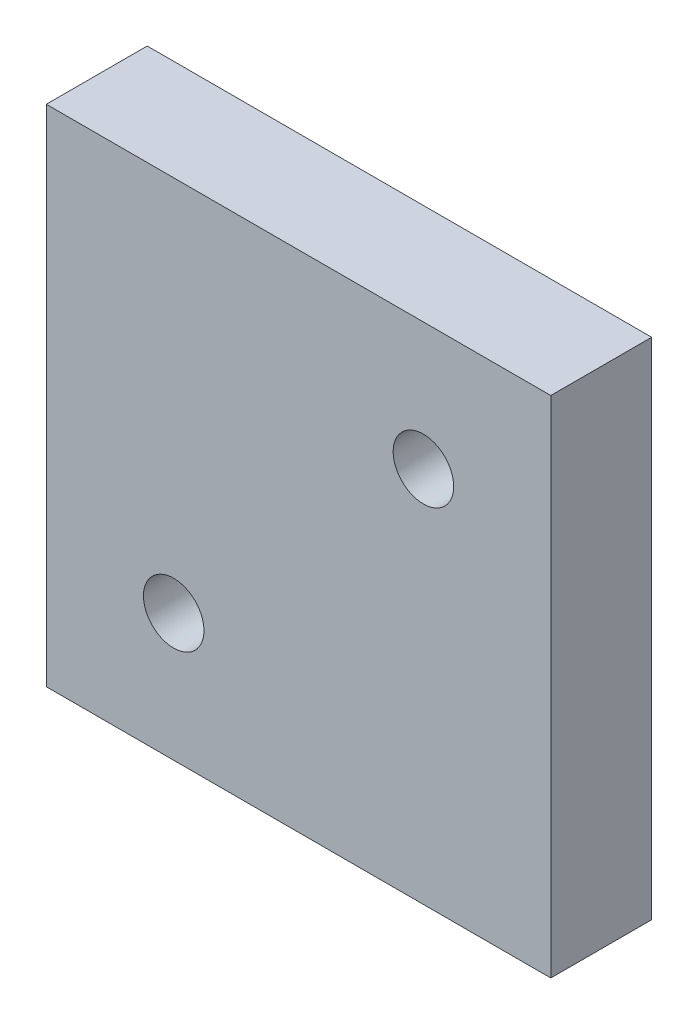
SolidWorks part; units mm, degrees
ref_plane "Спереди" through (0, 0, 0) normal (0, 0, 1) x (1, 0, 0)
ref_plane "Сверху" through (0, 0, 0) normal (0, 1, 0) x (1, 0, 0)
ref_plane "Справа" through (0, 0, 0) normal (1, 0, 0) x (0, 0, -1)
sketch "Эскиз1" plane through (0, 0, 0) normal (0, 0, 1) x (1, 0, 0)
  line L0 (24.7487, 24.7487) -> (-24.7487, -24.7487)
  line L1 (-50, 50) -> (50, 50)
  line L2 (-50, 50) -> (-50, -50)
  line L3 (-50, -50) -> (50, -50)
  line L4 (50, 50) -> (50, -50)
  line L5 (-50, 50) -> (50, -50) construction
  line L6 (-50, -50) -> (50, 50) construction
  point P0 (0, 0)
  point P9 (0, 0)
  dimension "D1" = 100
  dimension "D2" = 100
  dimension "D3" = 70
extrude "Бобышка-Вытянуть1" add sketch "Эскиз1" along normal blind 20
hole_wizard "Диаметр отверстия Ø12.0 (12)1" positions "Эскиз2" profile "Эскиз3" hole size "Ø12.0" standard "ISO" end condition through all
sketch "Эскиз2" plane through (0, 0, 0) normal (0, 0, -1) x (-1, 0, 0)
  point P0 (-24.7487, 24.7487)
  point P3 (24.7487, -24.7487)
sketch "Эскиз3" plane through (24.7487, 24.7487, 0) normal (1, 0, 0) x (0, 1, 0)
  line L0 (0, 0) -> (0, 20)
  line L1 (0, 20) -> (6, 20)
  line L2 (6, 20) -> (6, 0)
  line L5 (6, 0) -> (0, 0)
  line L11 (0, -6.35) -> (0, 107.95) construction
  dimension "Диаметр сквозного отверстия" = 12
  dimension "Глубина сквозного отверстия" = 20
